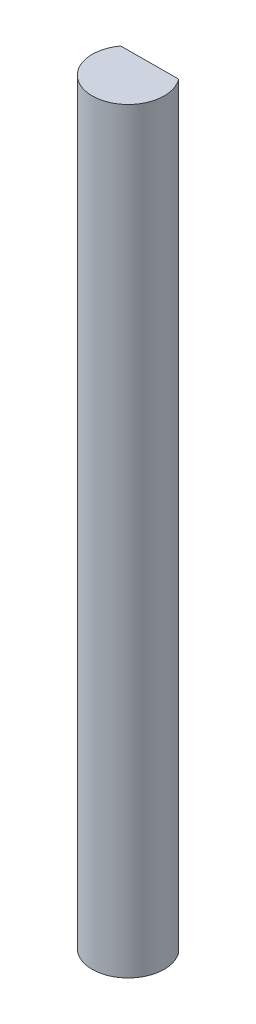
SolidWorks part; units mm, degrees
material "Plain Carbon Steel"
ref_plane "Front Plane" through (0, 0, 0) normal (0, 0, 1) x (1, 0, 0)
ref_plane "Top Plane" through (0, 0, 0) normal (0, 1, 0) x (1, 0, 0)
ref_plane "Right Plane" through (0, 0, 0) normal (1, 0, 0) x (0, 0, -1)
sketch "Sketch1" plane through (0, 0, 0) normal (0, 1, 0) x (1, 0, 0)
  circle A0 centre (0, 0) radius 3.175
  dimension "D1" = 6.35
extrude "Boss-Extrude1" add sketch "Sketch1" along normal mid plane 82.55
sketch "Sketch2" plane through (0, 41.275, 0) normal (0, 1, 0) x (1, 0, 0)
  line L0 (-2.5493, 1.8925) -> (2.5307, 1.9174)
  circle A0 centre (0, 0) radius 3.175 construction
  arc A1 (-2.5493, 1.8925) -> (2.5307, 1.9174) centre (0, 0) cw
  dimension "D1" = 5.08
extrude "Cut-Extrude5" cut sketch "Sketch2" against normal through all contours L0 A1
sketch "Sketch3" [suppressed] plane through (0, 41.275, 0) normal (0, 1, 0) x (1, 0, 0)
  line L1 (2.5307, 1.9174) -> (-2.5493, 1.8925)
  line L2 (2.5307, 1.9174) -> (-2.5493, 1.8925)
  arc A1 (-2.5493, 1.8925) -> (2.5307, 1.9174) centre (0, 0) ccw
  arc A2 (-2.5493, 1.8925) -> (2.5307, 1.9174) centre (0, 0) ccw
  dimension "D1" = 0
extrude "Cut-Extrude6" [suppressed] cut sketch "Sketch3" against normal blind 25.4
sketch "Sketch4" [suppressed] plane through (0, 41.275, 0) normal (0, 1, 0) x (1, 0, 0)
  line L1 (2.5307, 1.9174) -> (-2.5493, 1.8925)
  line L2 (2.5307, 1.9174) -> (-2.5493, 1.8925)
  arc A1 (-2.5493, 1.8925) -> (2.5307, 1.9174) centre (0, 0) ccw
  arc A2 (-2.5493, 1.8925) -> (2.5307, 1.9174) centre (0, 0) ccw
  dimension "D1" = 0
extrude "Cut-Extrude7" [suppressed] cut sketch "Sketch4" against normal blind 9.525
sketch "Sketch5" plane through (0, 41.275, 0) normal (0, 1, 0) x (1, 0, 0)
  line L1 (2.5307, 1.9174) -> (-2.5493, 1.8925)
  line L2 (2.5307, 1.9174) -> (-2.5493, 1.8925)
  arc A1 (-2.5493, 1.8925) -> (2.5307, 1.9174) centre (0, 0) ccw
  arc A2 (-2.5493, 1.8925) -> (2.5307, 1.9174) centre (0, 0) ccw
  dimension "D1" = 0
extrude "Cut-Extrude8" cut sketch "Sketch5" against normal blind 15.875
